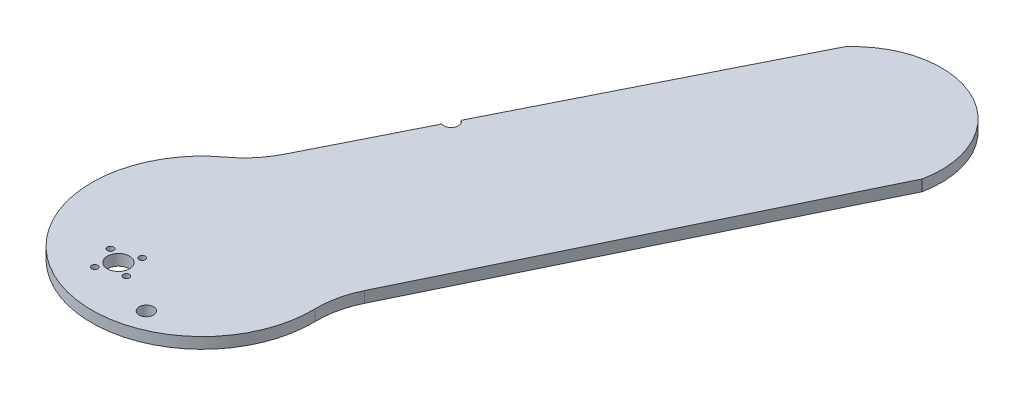
SolidWorks part; units mm, degrees
ref_plane "前视基准面" through (0, 0, 0) normal (0, 0, 1) x (1, 0, 0)
ref_plane "上视基准面" through (0, 0, 0) normal (0, 1, 0) x (1, 0, 0)
ref_plane "右视基准面" through (0, 0, 0) normal (1, 0, 0) x (0, 0, -1)
other "Configuration Table"
sketch "草图1" plane through (0, 0, 0) normal (0, 1, 0) x (1, 0, 0)
  line L0 (0, 0) -> (-22113.3564, -44843.3392) construction
  line L3 (-17.565, 54.5786) -> (67.0599, 223.4237)
  line L4 (53.9923, 19.2919) -> (136.4242, 189.2185)
  arc A0 (-29.625, 40.2786) -> (49.9896, 1.0186) centre (0, 0) ccw
  arc A1 (136.4242, 189.2185) -> (67.0599, 223.4237) centre (97.2176, 197.1461) ccw
  arc A2 (53.9923, 19.2919) -> (49.9896, 1.0186) centre (89.9813, 1.8336) ccw
  arc A3 (-29.625, 40.2786) -> (-17.565, 54.5786) centre (-53.3249, 72.5014) ccw
  point P10 (12.5434, 25.4366)
  point P13 (49.1325, 9.2736)
  point P16 (-22.5542, 44.6241)
  dimension "D1" = 100
  dimension "D4" = 40
  dimension "D5" = 40
  dimension "D2" = 40
  dimension "D3" = 200
  dimension "D6" = 168.8452
extrude "凸台-拉伸1" add sketch "草图1" along normal blind 5
sketch "草图2" plane through (0, 0, 0) normal (0, -1, 0) x (1, 0, 0)
  circle A0 centre (12.6514, 37.9466) radius 3.25
  circle A1 centre (81.5964, -36.1903) radius 3.25
  circle A2 centre (7.4596, -105.1353) radius 3.25
  circle A3 centre (-61.4854, -30.9985) radius 3.25
  point P12 (10.0555, -33.5944)
  dimension "D1" = 6.5
  dimension "D2" = 4
extrude "切除-拉伸1" cut sketch "草图2" against normal blind 19
sketch "草图3" plane through (0, 0, 0) normal (0, -1, 0) x (1, 0, 0)
  line L0 (-37.9466, 12.6514) -> (12.6514, 37.9466) construction
  line L1 (0, 0) -> (-12.6476, 25.299) construction
  circle A1 centre (-12.6476, 25.299) radius 5
  circle A2 centre (-19.8032, 21.7217) radius 1.4
  circle A3 centre (-5.492, 28.8763) radius 1.4
  circle A4 centre (-16.2249, 32.4546) radius 1.4
  circle A5 centre (-9.0703, 18.1434) radius 1.4
  circle A6 centre (-5.492, 28.8763) radius 1.4
  circle A7 centre (-19.8032, 21.7217) radius 1.4
  circle A8 centre (-9.0703, 18.1434) radius 1.4
  circle A9 centre (-16.2249, 32.4546) radius 1.4
  point P26 (-12.6476, 25.299)
  dimension "D2" = 2.8
  dimension "D1" = 10
  dimension "D3" = 2.8
  dimension "D5" = 8
  dimension "D4" = 8
extrude "切除-拉伸3" cut sketch "草图3" against normal blind 16.3 contours A4 | A2 | A1 | A3 | A5
sketch "草图4" plane through (0, 0, 0) normal (0, -1, 0) x (1, 0, 0)
  line L9 (-13.7635, -52.977) -> (70.6464, -221.8222)
  line L10 (135.0471, -189.6267) -> (50.6372, -20.7815)
  line L11 (53.9923, -19.2919) -> (136.4242, -189.2185)
  line L12 (67.0599, -223.4237) -> (9.2552, -108.0908)
  line L13 (53.9923, -19.2919) -> (136.4242, -189.2185)
  line L14 (67.0599, -223.4237) -> (9.2552, -108.0908)
  arc A13 (70.6464, -221.8222) -> (135.0471, -189.6267) centre (102.8467, -205.7245) ccw
  arc A14 (45.9965, -0.5656) -> (50.6372, -20.7815) centre (89.9932, -1.1065) ccw
  arc A15 (45.9965, -0.5656) -> (-27.15, -37.1333) centre (0, 0) ccw
  arc A16 (-13.7635, -52.977) -> (-27.15, -37.1333) centre (-53.1195, -72.6521) ccw
  arc A17 (67.0599, -223.4237) -> (136.4242, -189.2185) centre (97.2176, -197.1461) ccw
  arc A18 (49.9896, -1.0186) -> (53.9923, -19.2919) centre (89.9813, -1.8336) ccw
  arc A19 (49.9896, -1.0186) -> (-29.625, -40.2786) centre (0, 0) ccw
  arc A20 (-17.565, -54.5786) -> (-29.625, -40.2786) centre (-53.3249, -72.5014) ccw
  arc A21 (67.0599, -223.4237) -> (136.4242, -189.2185) centre (97.2176, -197.1461) ccw
  arc A22 (49.9896, -1.0186) -> (53.9923, -19.2919) centre (89.9813, -1.8336) ccw
  arc A23 (49.9896, -1.0186) -> (-29.625, -40.2786) centre (0, 0) ccw
  arc A24 (-17.565, -54.5786) -> (-29.625, -40.2786) centre (-53.3249, -72.5014) ccw
  dimension "D1" = 0
  dimension "D2" = 4
